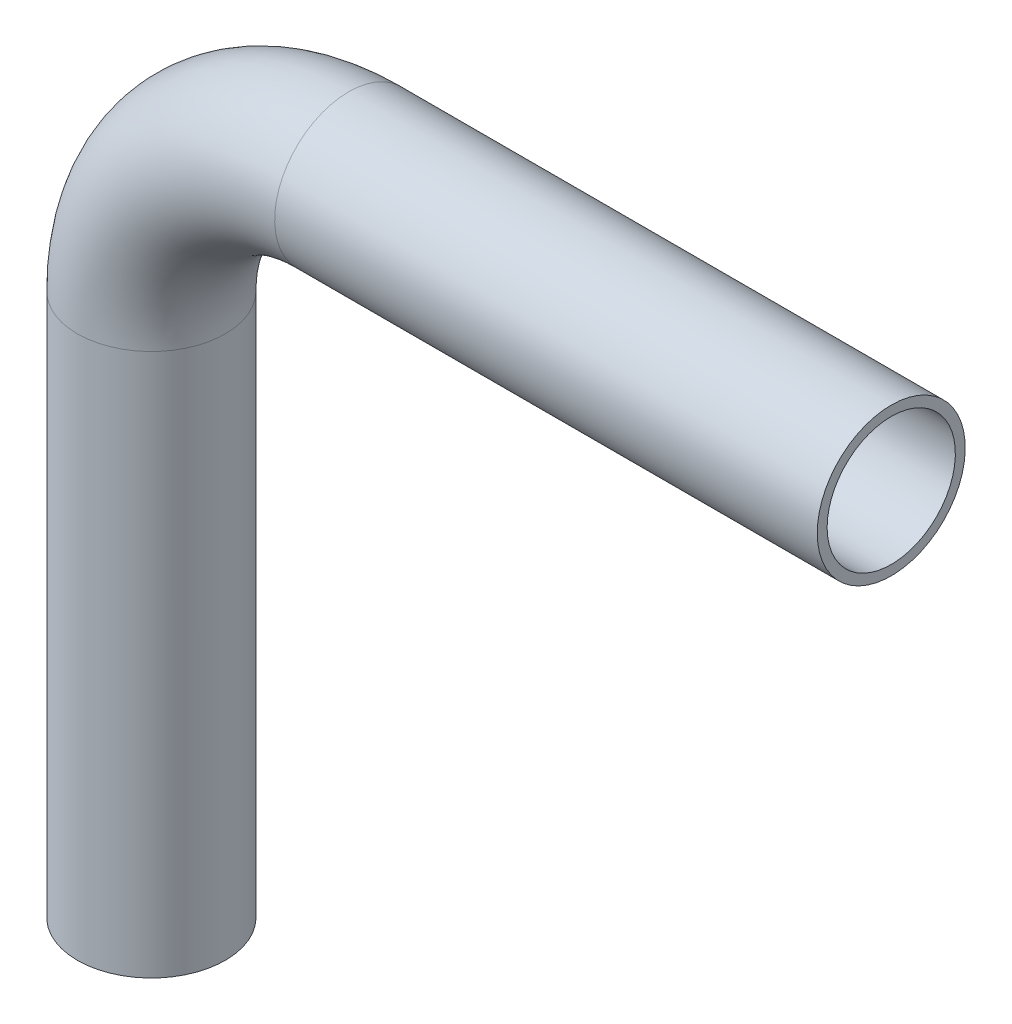
SolidWorks part; units mm, degrees
ref_plane "Plano frontal" through (0, 0, 0) normal (0, 0, 1) x (1, 0, 0)
ref_plane "Plano superior" through (0, 0, 0) normal (0, 1, 0) x (1, 0, 0)
ref_plane "Plano direito" through (0, 0, 0) normal (1, 0, 0) x (0, 0, -1)
sketch "Esboço1" plane through (0, 0, 0) normal (0, 0, 1) x (1, 0, 0)
  line L0 (0, 0) -> (0, 110)
  line L1 (40, 150) -> (150, 150)
  arc A0 (40, 150) -> (0, 110) centre (40, 110) ccw
  point P6 (0, 150)
  dimension "D3" = 40
  dimension "D1" = 150
  dimension "D2" = 150
sketch "Esboço2" plane through (0, 0, 0) normal (0, 1, 0) x (1, 0, 0)
  circle A0 centre (0, 0) radius 15
  circle A1 centre (0, 0) radius 13
  dimension "D1" = 30
  dimension "D2" = 2
sweep "Varredura1" add profiles "Esboço2" path "Esboço1"
